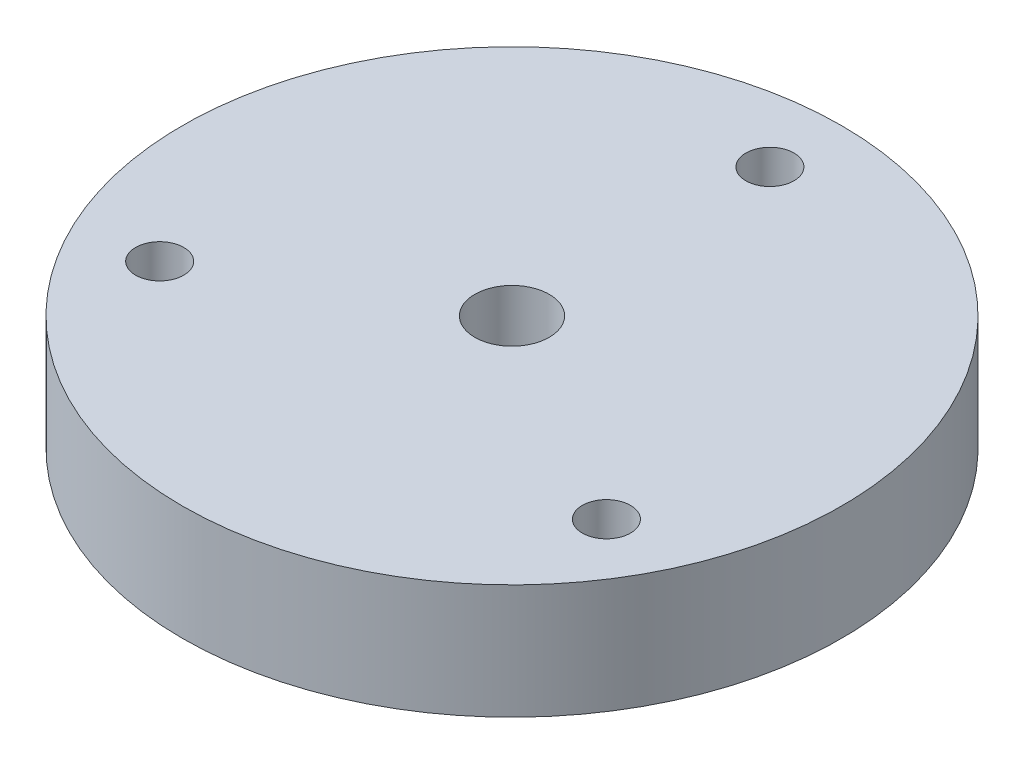
SolidWorks part; units mm, degrees
ref_plane "Front Plane" through (0, 0, 0) normal (0, 0, 1) x (1, 0, 0)
ref_plane "Top Plane" through (0, 0, 0) normal (0, 1, 0) x (1, 0, 0)
ref_plane "Right Plane" through (0, 0, 0) normal (1, 0, 0) x (0, 0, -1)
sketch "Sketch2" plane through (0, 0, 0) normal (0, 1, 0) x (1, 0, 0)
  line L0 (0, 0) -> (28.75, 0) construction
  line L3 (0, 28.75) -> (0, 22.5) construction
  circle A0 centre (0, 0) radius 28.75
  circle A6 centre (0, 0) radius 3.25
  circle A7 centre (0, 22.5) radius 2.1
  circle A8 centre (19.4856, -11.25) radius 2.1
  circle A9 centre (-19.4856, -11.25) radius 2.1
  point P13 (8.2994, -14.375)
  point P17 (0, 0)
  dimension "D3" = 4.2
  dimension "D4" = 3
  dimension "D2" = 6.25
  dimension "D1" = 28.75
extrude "Boss-Extrude1" add sketch "Sketch2" along normal blind 10
